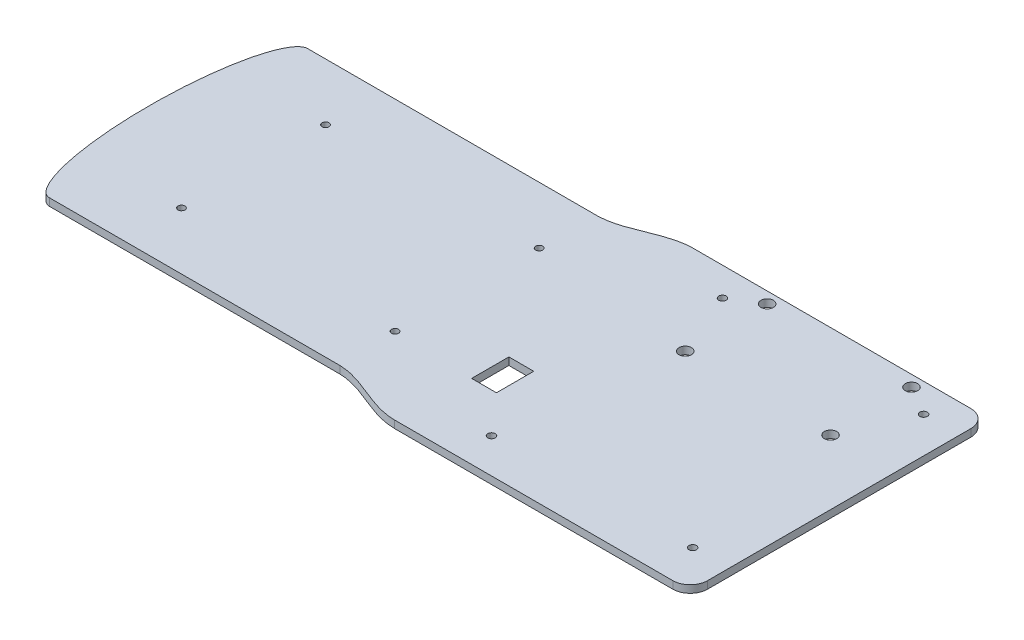
SolidWorks part; units mm, degrees
ref_plane "정면" through (0, 0, 0) normal (0, 0, 1) x (1, 0, 0)
ref_plane "윗면" through (0, 0, 0) normal (0, 1, 0) x (1, 0, 0)
ref_plane "우측면" through (0, 0, 0) normal (1, 0, 0) x (0, 0, -1)
sketch "스케치1" plane through (0, 0, 0) normal (0, 1, 0) x (1, 0, 0)
  line L1 (-139, 60) -> (139, 60)
  line L2 (-139, 60) -> (-139, -60)
  line L3 (-139, -60) -> (139, -60)
  line L4 (139, 60) -> (139, -60)
  line L5 (-139, 60) -> (139, -60) construction
  line L6 (-139, -60) -> (139, 60) construction
  point P0 (0, 0)
  dimension "D1" = 278
  dimension "D2" = 120
extrude "보스-돌출1" add sketch "스케치1" along normal blind 3
sketch "스케치2" plane through (0, 3, 0) normal (0, 1, 0) x (1, 0, 0)
  line L0 (-10, 60) -> (-10, -60) construction
  line L1 (139, 60) -> (-139, 60) construction
  line L2 (-139, -60) -> (139, -60) construction
  line L3 (-139, 60) -> (-139, -60) construction
  line L4 (20, 60) -> (20, -60) construction
  line L5 (-139, 0) -> (-10, 0) construction
  line L6 (-127, 60) -> (-127, -60) construction
  line L7 (-139, -52) -> (-10, -52) construction
  line L8 (-139, -52) -> (-139, 52) construction
  line L9 (-139, 52) -> (-10, 52) construction
  line L10 (-10, -52) -> (-10, 52) construction
  line L11 (-139, -52) -> (-10, 52) construction
  line L12 (-139, 52) -> (-10, -52) construction
  line L14 (-139, -52) -> (-10, -52)
  line L15 (-139, -52) -> (-139, -60)
  line L16 (-139, -60) -> (-10, -60)
  line L17 (-10, -52) -> (-10, -60)
  line L18 (-10, 60) -> (-139, 60)
  line L19 (-10, 60) -> (-10, 52)
  line L20 (-10, 52) -> (-139, 52)
  line L21 (-139, 60) -> (-139, 52)
  point P12 (-74.5, 0)
  dimension "D1" = 129
  dimension "D2" = 159
  dimension "D3" = 104
  dimension "D4" = 12
extrude "컷-돌출1" cut sketch "스케치2" against normal blind 3
sketch "스케치3" plane through (0, 3, 0) normal (0, 1, 0) x (1, 0, 0)
  line L0 (-127, 52) -> (-127, -52) construction
  line L1 (-139, 52) -> (-10, 52) construction
  line L2 (-10, -52) -> (-139, -52) construction
  line L3 (-139, 52) -> (-139, -52) construction
  line L4 (-127, 52) -> (-139, 52)
  line L5 (-139, 52) -> (-139, 0)
  line L6 (-139, 0) -> (-139, -52)
  line L7 (-139, -52) -> (-127, -52)
  ellipse E0 centre (-127, 0) end of major axis (-127, -52) minor radius 12
  line M2 (-10, 52) -> (-139, 52)
  line M3 (-139, 52) -> (-139, -52)
  line M4 (-139, -52) -> (-10, -52)
  dimension "D1" = 12
extrude "컷-돌출2" cut sketch "스케치3" against normal blind 3 contours E0 M2 M3 | E0 M3 M4
sketch "스케치4" plane through (0, 3, 0) normal (0, 1, 0) x (1, 0, 0)
  line L0 (20, 60) -> (20, -60) construction
  line L1 (139, 60) -> (-10, 60) construction
  line L2 (-10, -60) -> (139, -60) construction
  line L3 (-10, 52) -> (-10, -52) construction
  line L4 (-10, -52) -> (-127, -52) construction
  line L5 (139, 0) -> (-139, 0) construction
  line L6 (139, -60) -> (139, 60) construction
  line L7 (-10, 52) -> (-10, 60)
  line L8 (-10, 60) -> (20, 60)
  line L9 (-10, -52) -> (-10, -60)
  line L10 (-10, -60) -> (20, -60)
  ellipse E0 centre (-127, 0) end of major axis (-127, -52) minor radius 12 (-127, 52) -> (-127, -52) ccw construction
  spline S0 degree 3 poles (-10, 52) (0.6412, 52.3672) (9.3767, 59.9199) (20, 60) knots 0 0 0 0 1 1 1 1
  spline S1 degree 3 poles (-10, -52) (0.6412, -52.3672) (9.3767, -59.9199) (20, -60) knots 0 0 0 0 1 1 1 1
  dimension "D1" = 30
extrude "컷-돌출4" cut sketch "스케치4" against normal blind 3
sketch "스케치5" plane through (0, 3, 0) normal (0, 1, 0) x (1, 0, 0)
  line L0 (139, 0) -> (-139, 0) construction
  line L1 (139, -60) -> (139, 60) construction
  line L2 (139, 60) -> (20, 60) construction
  line L3 (132, 60) -> (139, 60)
  line L4 (139, 60) -> (139, 53)
  line L5 (139, -60) -> (139, -53)
  line L6 (132, -60) -> (139, -60)
  arc A0 (139, 53) -> (132, 60) centre (132, 53) ccw
  arc A1 (139, -53) -> (132, -60) centre (132, -53) cw
  ellipse E0 centre (-127, 0) end of major axis (-127, -52) minor radius 12 (-127, 52) -> (-127, -52) ccw construction
  dimension "D1" = 14
extrude "컷-돌출5" cut sketch "스케치5" against normal blind 3
sketch "스케치16" plane through (0, 3, 0) normal (0, 1, 0) x (1, 0, 0)
  line L0 (-127, 52) -> (-10, 52) construction
  line L1 (-106, -49) -> (-106, 49) construction
  line L2 (-106, 49) -> (4.3, 49) construction
  line L3 (-106, -49) -> (4.3, -49) construction
  line L4 (4.3, 49) -> (4.3, -49) construction
  circle A0 centre (-96.8513, 29.0311) radius 1.3998
  circle A1 centre (-96.8511, -28.968) radius 1.3998
  circle A2 centre (-10.8522, 29.0327) radius 1.3998
  circle A3 centre (-10.8511, -28.9678) radius 1.3998
  point P0 (-96.8511, -28.968)
  point P1 (-10.8511, -28.9678)
  point P2 (-10.8522, 29.0327)
  point P14 (4.3, 0)
  point P15 (-96.8513, 29.0311)
  dimension "D11" = 2.7996
  dimension "D12" = 2.7996
  dimension "D13" = 2.7996
  dimension "D14" = 2.7996
  dimension "D1" = 9.1487
  dimension "D2" = 98
  dimension "D3" = 110.3
  dimension "D4" = 19.9689
  dimension "D5" = 9.1489
  dimension "D6" = 20.032
  dimension "D7" = 20.0322
  dimension "D8" = 15.1511
  dimension "D9" = 15.1522
  dimension "D10" = 19.9673
  dimension "D15" = 22.9689
extrude "컷-돌출9" cut sketch "스케치16" against normal blind 10
sketch "스케치17" plane through (0, 3, 0) normal (0, 1, 0) x (1, 0, 0)
  line L0 (139, 0) -> (-139, 0) construction
  line L1 (139, -53) -> (139, 53) construction
  line L2 (-196.5554, 54) -> (178.1376, 54)
  line L3 (-196.5554, -54) -> (178.1376, -54)
  ellipse E0 centre (-127, 0) end of major axis (-127, -52) minor radius 12 (-127, 52) -> (-127, -52) ccw construction
  dimension "D1" = 54
sketch "스케치18" plane through (0, 3, 0) normal (0, 1, 0) x (1, 0, 0)
  line L0 (139, -53) -> (139, 53) construction
  line L1 (21, -15) -> (31, -15)
  line L2 (21, -15) -> (21, -30)
  line L3 (21, -30) -> (31, -30)
  line L4 (31, -15) -> (31, -30)
  line L5 (132, 60) -> (20, 60) construction
  dimension "D1" = 108
  dimension "D2" = 75
  dimension "D3" = 15
  dimension "D4" = 10
extrude "컷-돌출10" cut sketch "스케치18" against normal blind 10
sketch "스케치19" plane through (0, 3, 0) normal (0, 1, 0) x (1, 0, 0)
  line L0 (139, -53) -> (139, 53) construction
  line L1 (132, 60) -> (20, 60) construction
  circle A0 centre (112.6, 55.5) radius 2.5
  dimension "D1" = 5
  dimension "D2" = 26.4
  dimension "D3" = 4.5
extrude "컷-돌출11" cut sketch "스케치19" against normal blind 10
sketch "스케치20" plane through (0, 3, 0) normal (0, 1, 0) x (1, 0, 0)
  line L0 (132, 60) -> (20, 60) construction
  line L1 (139, -53) -> (139, 53) construction
  circle A0 centre (124.5, 48.5) radius 1.5
  dimension "D1" = 3
  dimension "D2" = 11.5
  dimension "D3" = 14.5
extrude "컷-돌출12" cut sketch "스케치20" against normal blind 10
sketch "스케치21" plane through (0, 3, 0) normal (0, 1, 0) x (1, 0, 0)
  line L0 (20, -60) -> (132, -60) construction
  line L1 (139, -53) -> (139, 53) construction
  circle A0 centre (124.5, -44.5) radius 1.5
  dimension "D1" = 3
  dimension "D2" = 15.5
  dimension "D3" = 14.5
extrude "컷-돌출13" cut sketch "스케치21" against normal blind 10
sketch "스케치22" plane through (0, 3, 0) normal (0, 1, 0) x (1, 0, 0)
  line L0 (132, 60) -> (20, 60) construction
  line L1 (139, -53) -> (139, 53) construction
  circle A0 centre (54.5, 55.5) radius 2.5
  dimension "D1" = 5
  dimension "D2" = 4.5
  dimension "D3" = 84.5
extrude "컷-돌출14" cut sketch "스케치22" against normal blind 10
sketch "스케치23" plane through (0, 3, 0) normal (0, 1, 0) x (1, 0, 0)
  line L0 (139, -53) -> (139, 53) construction
  line L1 (132, 60) -> (20, 60) construction
  circle A0 centre (113, 22.5) radius 2.5
  circle A1 centre (54.5, 22.5) radius 2.5
  dimension "D1" = 5
  dimension "D3" = 5
  dimension "D2" = 26
  dimension "D4" = 84.5
  dimension "D5" = 37.5
  dimension "D6" = 37.5
extrude "컷-돌출15" cut sketch "스케치23" against normal blind 10
sketch "스케치24" plane through (0, 3, 0) normal (0, 1, 0) x (1, 0, 0)
  line L0 (20, -60) -> (132, -60) construction
  line L1 (139, -53) -> (139, 53) construction
  circle A0 centre (45, -46) radius 1.5
  dimension "D1" = 3
  dimension "D2" = 14
  dimension "D3" = 94
extrude "컷-돌출16" cut sketch "스케치24" against normal blind 10
sketch "스케치25" plane through (0, 3, 0) normal (0, 1, 0) x (1, 0, 0)
  line L0 (132, 60) -> (20, 60) construction
  line L1 (139, -53) -> (139, 53) construction
  circle A0 centre (43.5, 48.5) radius 1.5
  dimension "D1" = 3
  dimension "D2" = 11.5
  dimension "D3" = 95.5
extrude "컷-돌출17" cut sketch "스케치25" against normal blind 10
